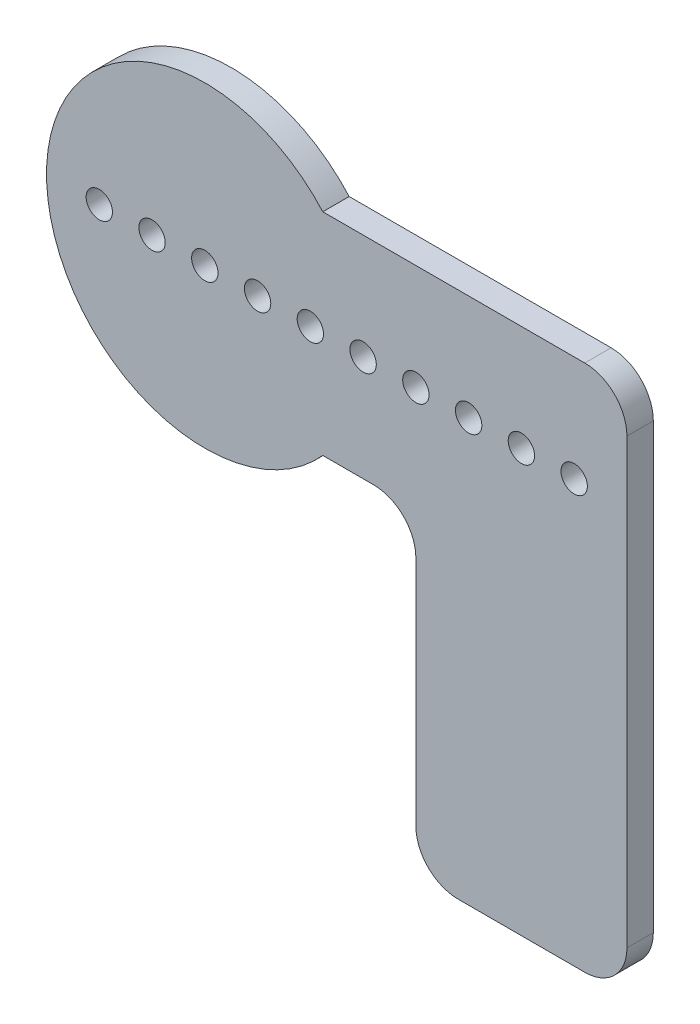
SolidWorks part; units mm, degrees
ref_plane "Front Plane" through (0, 0, 0) normal (0, 0, 1) x (1, 0, 0)
ref_plane "Top Plane" through (0, 0, 0) normal (0, 1, 0) x (1, 0, 0)
ref_plane "Right Plane" through (0, 0, 0) normal (1, 0, 0) x (0, 0, -1)
sketch "Sketch1" plane through (0, 0, 0) normal (0, 0, 1) x (1, 0, 0)
  line L1 (0, 0) -> (-25.4, 0)
  line L2 (0, 0) -> (0, 63.5)
  line L3 (0, 63.5) -> (-25.4, 63.5)
  line L4 (-25.4, 0) -> (-25.4, 63.5)
  line L5 (-25.4, 63.5) -> (-50.8, 63.5)
  line L7 (-25.4, 38.1) -> (-50.8, 38.1)
  line L8 (-50.8, 63.5) -> (-50.8, 38.1)
  circle A0 centre (-50.8, 50.8) radius 19.05
  dimension "D5" = 38.1
  dimension "D1" = 63.5
  dimension "D2" = 25.4
  dimension "D3" = 25.4
  dimension "D4" = 25.4
extrude "Boss-Extrude1" add sketch "Sketch1" along normal blind 3.175 contours L5 A0 L7 L8 | L7 A0 L5 L8 | A0 L7 L4 L5 | L4 L1 L2 L3
fillet "Fillet1" radius 5.08 4 edges at (0, 0, 1.5875) (-25.4, 0, 1.5875) (-25.4, 38.1, 1.5875) (0, 63.5, 1.5875)
sketch "Sketch2" plane through (0, 0, 3.175) normal (0, 0, 1) x (1, 0, 0)
  line L0 (-5.08, 63.5) -> (-36.601, 63.5) construction
  line L1 (0, 5.08) -> (0, 58.42) construction
  circle A0 centre (-6.35, 50.8) radius 1.5875
  circle A1 centre (-12.7, 50.8) radius 1.5875
  circle A2 centre (-19.05, 50.8) radius 1.5875
  circle A3 centre (-25.4, 50.8) radius 1.5875
  circle A4 centre (-31.75, 50.8) radius 1.5875
  circle A5 centre (-38.1, 50.8) radius 1.5875
  circle A6 centre (-44.45, 50.8) radius 1.5875
  circle A7 centre (-50.8, 50.8) radius 1.5875
  circle A8 centre (-57.15, 50.8) radius 1.5875
  circle A9 centre (-63.5, 50.8) radius 1.5875
  dimension "D3" = 3.175
  dimension "D1" = 12.7
  dimension "D2" = 6.35
  dimension "D4" = 10
extrude "Cut-Extrude1" cut sketch "Sketch2" against normal blind 3.175
